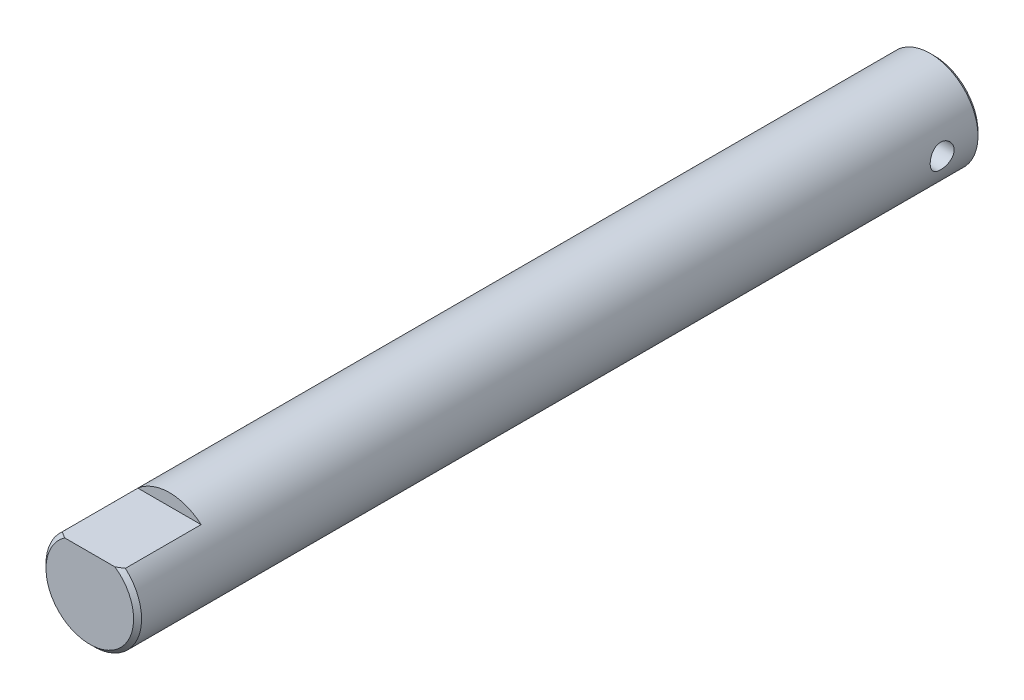
SolidWorks part; units mm, degrees
ref_plane "Front Plane" through (0, 0, 0) normal (0, 0, 1) x (1, 0, 0)
ref_plane "Top Plane" through (0, 0, 0) normal (0, 1, 0) x (1, 0, 0)
ref_plane "Right Plane" through (0, 0, 0) normal (1, 0, 0) x (0, 0, -1)
sketch "Sketch1" plane through (0, 0, 0) normal (0, 0, 1) x (1, 0, 0)
  circle A0 centre (0, 0) radius 6
  dimension "D1" = 12
extrude "Boss-Extrude1" add sketch "Sketch1" along normal mid plane 106
chamfer "Chamfer1" distance 0.5 angle 45 2 edges at (6, 0, -53) (6, 0, 53)
sketch "Sketch2" plane through (0, 0, 0) normal (1, 0, 0) x (0, 0, -1)
  line L0 (53, -5.5) -> (53, 5.5) construction
  circle A0 centre (48, 0) radius 1.5
  dimension "D1" = 3
  dimension "D2" = 5
extrude "Cut-Extrude1" cut sketch "Sketch2" against normal through all both and the other way through all
sketch "Sketch3" plane through (0, 0, 0) normal (0, 1, 0) x (1, 0, 0)
  line L0 (-5.5, -53) -> (5.5, -53) construction
  line L1 (6.9521, -53) -> (-5.0479, -53)
  line L2 (6.9521, -53) -> (6.9521, -43)
  line L3 (6.9521, -43) -> (-5.0479, -43)
  line L4 (-5.0479, -53) -> (-5.0479, -43)
  line L5 (6.9521, -53) -> (-5.0479, -43) construction
  line L6 (6.9521, -43) -> (-5.0479, -53) construction
  point P0 (0.9521, -48)
  dimension "D1" = 12
  dimension "D2" = 10
extrude "Cut-Extrude2" cut sketch "Sketch3" along normal blind 10 from offset 4.5
